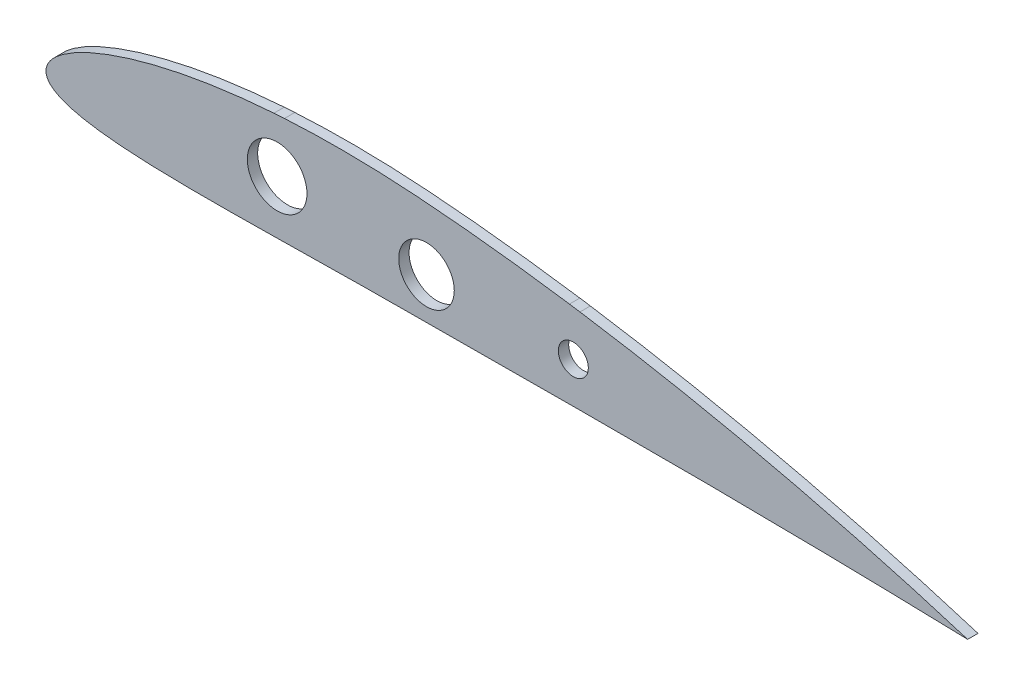
SolidWorks part; units mm, degrees
material "Фанера"
ref_plane "Front Plane" through (0, 0, 0) normal (0, 0, 1) x (1, 0, 0)
ref_plane "Top Plane" through (0, 0, 0) normal (0, 1, 0) x (1, 0, 0)
ref_plane "Right Plane" through (0, 0, 0) normal (1, 0, 0) x (0, 0, -1)
sketch "Эскиз1" plane through (0, 0, 0) normal (0, 0, 1) x (1, 0, 0)
  line L0 (150.3512, 128.259) -> (147.6767, 128.661)
  line L1 (255.981, 105.8183) -> (150.7263, 130.2251) construction
  line L2 (69.8251, 105.8135) -> (147.0441, 106.4426) construction
  line L3 (6.1919, 114.8477) -> (66.9719, 105.7712) construction
  line L4 (68.006, 135.3847) -> (6.1919, 114.8477) construction
  line L5 (68.3924, 133.4055) -> (14.7673, 115.5893) construction
  line L6 (69.8021, 107.8133) -> (147.0317, 108.4426) construction
  line L7 (147.8895, 130.6515) -> (70.8642, 135.5703) construction
  line L8 (67.001, 103.7714) -> (69.8554, 103.8137) construction
  line L9 (70.7405, 137.5665) -> (67.8703, 137.3801) construction
  line L10 (151.028, 132.2022) -> (148.1867, 132.6293) construction
  line L11 (147.0528, 104.4426) -> (149.9045, 104.4548) construction
  line L12 (147.6767, 128.661) -> (70.8653, 133.5662) construction
  line L13 (240.4166, 107.3743) -> (150.3512, 128.259) construction
  line L14 (149.8962, 106.4548) -> (255.959, 105.1887) construction
  line L15 (149.9039, 108.4548) -> (240.4166, 107.3743) construction
  line L16 (150.7263, 130.2251) -> (147.8895, 130.6515) construction
  line L17 (147.0441, 106.4426) -> (149.8962, 106.4548) construction
  line L18 (66.9719, 105.7712) -> (69.8251, 105.8135) construction
  line L19 (70.8642, 135.5703) -> (68.006, 135.3847) construction
  line L20 (67.1056, 107.7734) -> (69.8021, 107.8133) construction
  line L21 (70.8653, 133.5662) -> (68.3924, 133.4055) construction
  line L22 (147.0317, 108.4426) -> (149.9039, 108.4548) construction
  line L23 (14.7673, 115.5893) -> (67.1056, 107.7734) construction
  line L24 (150.6664, 129.8296) -> (147.8304, 130.2559)
  line L25 (70.8877, 135.171) -> (68.0343, 134.9857)
  line L26 (66.966, 106.1712) -> (69.8191, 106.2134)
  line L27 (147.0423, 106.8426) -> (149.8946, 106.8548)
  arc A0 (240.4166, 107.3743) -> (240.4166, 107.3743) centre (240.4166, 107.3743) ccw
  arc A1 (255.3129, 105.6068) -> (255.3129, 105.6068) centre (255.3129, 105.6068) ccw
  circle A2 centre (148.8681, 117.845) radius 4.05
  circle A3 centre (109.2326, 117.845) radius 7.5
  circle A4 centre (68.9168, 120.6369) radius 8.05
  arc A6 (256.3721, 103.1764) -> (256.8714, 107.636) centre (255.6552, 105.5145) ccw construction
  arc A8 (255.959, 105.1887) -> (255.981, 105.8183) centre (255.6552, 105.5145) ccw construction
  spline S0 degree 1 poles (147.8304, 130.2559) (70.8877, 135.171) knots 0 0 1 1 construction
  spline S1 degree 1 poles (68.0343, 134.9857) (6.5854, 114.7729) knots 0 0 1 1 construction
  spline S2 degree 1 poles (6.5854, 114.7729) (66.966, 106.1712) knots 0 0 1 1 construction
  spline S3 degree 1 poles (69.8191, 106.2134) (147.0423, 106.8426) knots 0 0 1 1 construction
  spline S4 degree 1 poles (149.8946, 106.8548) (255.3129, 105.6068) knots 0 0 1 1 construction
  spline S5 degree 1 poles (255.3129, 105.6068) (150.6664, 129.8296) knots 0 0 1 1 construction
  spline S6 degree 3 poles (147.8304, 130.2559) (141.4614, 131.1985) (128.6934, 132.8864) (112.6704, 134.4616) (99.827, 135.315) (86.964, 135.7313) (77.3083, 135.5495) (70.8877, 135.171) knots 0.429725 0.429725 0.429725 0.429725 0.504545 0.579365 0.616774 0.654184 0.729004 0.729004 0.729004 0.729004
  spline S7 degree 3 poles (68.0343, 134.9857) (62.4663, 134.5901) (54.1288, 133.7002) (43.1252, 131.8029) (34.9538, 129.9771) (26.9072, 127.676) (20.368, 125.2621) (15.3365, 122.8884) (11.7396, 120.808) (8.9915, 118.6964) (7.4817, 116.8862) (6.9154, 115.8582) (6.7079, 115.2743) (6.6255, 114.9369) (6.5854, 114.7729) knots 0.740091 0.740091 0.740091 0.740091 0.805048 0.837527 0.870006 0.902484 0.934963 0.951202 0.967442 0.983681 0.991801 0.995861 0.99789 0.99992 0.99992 0.99992 0.99992
  spline S8 degree 3 poles (6.5854, 114.7729) (6.5637, 114.6143) (6.519, 114.2854) (6.5148, 113.7109) (6.7419, 112.6615) (7.6602, 111.4099) (9.2591, 110.3083) (11.0446, 109.4874) (12.9222, 108.8501) (15.4901, 108.1728) (18.7685, 107.5586) (22.7454, 107.0432) (28.0773, 106.5574) (34.7696, 106.2135) (42.8135, 106.0372) (50.8627, 106.0061) (58.9136, 106.0623) (64.282, 106.1325) (66.966, 106.1712) knots 0.000081 0.000081 0.000081 0.000081 0.002067 0.004053 0.008026 0.01597 0.023915 0.031859 0.039804 0.047748 0.063637 0.079526 0.095416 0.127194 0.158972 0.19075 0.222528 0.254306 0.254306 0.254306 0.254306
  spline S9 degree 3 poles (69.8191, 106.2134) (76.2539, 106.311) (85.9048, 106.4721) (98.7779, 106.6108) (111.6511, 106.6495) (127.7354, 106.7325) (140.607, 106.8137) (147.0423, 106.8426) knots 0.265565 0.265565 0.265565 0.265565 0.341733 0.379817 0.417901 0.494069 0.570237 0.570237 0.570237 0.570237
  spline S10 degree 3 poles (149.8946, 106.8548) (158.6803, 106.89) (176.2516, 106.9163) (202.6097, 106.7306) (228.9647, 106.2926) (246.5305, 105.8506) (255.3129, 105.6068) knots 0.58149 0.58149 0.58149 0.58149 0.685469 0.789448 0.893427 0.997406 0.997406 0.997406 0.997406
  spline S11 degree 3 poles (255.3129, 105.6068) (246.7563, 108.2609) (229.5444, 113.257) (203.4702, 119.7998) (177.1786, 125.4044) (159.5222, 128.478) (150.6664, 129.8296) knots 0.002228 0.002228 0.002228 0.002228 0.106325 0.210423 0.31452 0.418617 0.418617 0.418617 0.418617
  spline S12 degree 3 poles (4.2245, 115.2218) (4.2126, 115.1351) (4.1901, 114.9728) (4.1369, 114.5596) (4.0997, 113.8715) (4.1934, 113.0746) (4.4478, 112.0722) (5.0329, 110.8962) (5.9577, 109.8121) (6.9592, 108.9756) (8.333, 108.0935) (10.0616, 107.291) (12.1329, 106.5788) (14.8842, 105.8458) (18.3089, 105.1999) (22.402, 104.6657) (26.4841, 104.2911) (30.5571, 104.0277) (35.978, 103.7862) (42.7402, 103.6379) (50.8379, 103.6058) (58.9249, 103.6622) (64.3084, 103.7327) (67.001, 103.7714) knots -0.000405 -0.000405 -0.000405 -0.000405 0.00059 0.001585 0.003575 0.005565 0.007555 0.011535 0.015514 0.019494 0.023474 0.031434 0.039394 0.047354 0.063273 0.079193 0.095112 0.111032 0.126952 0.158791 0.19063 0.222469 0.254308 0.254308 0.254308 0.254308 construction
  spline S13 degree 3 poles (67.8703, 137.3801) (65.0503, 137.1797) (59.4186, 136.6785) (50.9968, 135.5967) (42.6198, 134.1508) (34.309, 132.2908) (27.4644, 130.3322) (22.0663, 128.4455) (18.0689, 126.8357) (14.1437, 124.9752) (10.9598, 123.1311) (8.5154, 121.3532) (7.0522, 120.0467) (5.9644, 118.8218) (5.3324, 117.9305) (4.8996, 117.1691) (4.5854, 116.5037) (4.3875, 115.8781) (4.2866, 115.4769) (4.246, 115.3096) (4.2245, 115.2218) knots 0.740067 0.740067 0.740067 0.740067 0.772609 0.80515 0.837691 0.870232 0.902774 0.919044 0.935315 0.951586 0.967856 0.975992 0.984127 0.988195 0.992262 0.994296 0.99633 0.998364 0.999381 1.000398 1.000398 1.000398 1.000398 construction
  spline S14 degree 3 poles (148.1867, 132.6293) (141.7912, 133.5759) (128.9685, 135.2709) (112.884, 136.8527) (99.9444, 137.7126) (86.9715, 138.1325) (77.2213, 137.9485) (70.7405, 137.5665) knots 0.429706 0.429706 0.429706 0.429706 0.504536 0.579367 0.616782 0.654197 0.729027 0.729027 0.729027 0.729027 construction
  spline S15 degree 3 poles (256.8714, 107.636) (248.2169, 110.3216) (230.8173, 115.4068) (204.446, 122.039) (177.8555, 127.7216) (159.9886, 130.8346) (151.028, 132.2022) knots -0.001207 -0.001207 -0.001207 -0.001207 0.10375 0.208706 0.313663 0.418619 0.418619 0.418619 0.418619 construction
  spline S16 degree 3 poles (149.9045, 104.4548) (158.7785, 104.4903) (176.5281, 104.5165) (203.1441, 104.3248) (229.757, 103.8766) (247.5013, 103.4229) (256.3721, 103.1764) knots 0.581491 0.581491 0.581491 0.581491 0.686581 0.79167 0.89676 1.001849 1.001849 1.001849 1.001849 construction
  spline S17 degree 3 poles (69.8554, 103.8137) (76.2881, 103.9112) (85.9421, 104.0724) (98.7946, 104.2108) (111.6509, 104.2495) (127.7557, 104.3325) (140.6187, 104.4137) (147.0528, 104.4426) knots 0.265565 0.265565 0.265565 0.265565 0.341733 0.379817 0.4179 0.494068 0.570236 0.570236 0.570236 0.570236 construction
  spline S24 degree 3 poles (255.981, 105.8183) (255.1452, 106.0776) (252.7344, 106.8257) (248.4483, 108.1259) (242.96, 109.7477) (236.9465, 111.469) (230.6793, 113.2037) (224.3094, 114.9057) (217.8951, 116.5587) (211.4569, 118.157) (205.0023, 119.6987) (198.5346, 121.1828) (192.0557, 122.6086) (185.5671, 123.9752) (179.0705, 125.2817) (172.5672, 126.5268) (166.0589, 127.7093) (159.5471, 128.8277) (154.4349, 129.6536) (151.4938, 130.108) (150.7263, 130.2251) knots 0 0 0 0 0.010162 0.029313 0.052012 0.076619 0.101948 0.127526 0.153184 0.178868 0.204558 0.230246 0.255926 0.281594 0.307246 0.332878 0.358485 0.384061 0.409603 0.418619 0.418619 0.418619 0.418619 construction
  spline S25 degree 3 poles (149.8962, 106.4548) (151.0697, 106.4595) (154.5381, 106.4723) (160.2987, 106.4873) (167.1755, 106.4936) (174.0453, 106.4866) (180.9094, 106.465) (187.7693, 106.4278) (194.6263, 106.3745) (201.4814, 106.3045) (208.3355, 106.2177) (217.4659, 106.0799) (226.5694, 105.9098) (235.5825, 105.7122) (242.0508, 105.5578) (247.9425, 105.407) (252.5192, 105.2842) (255.0798, 105.2131) (255.959, 105.1887) knots 0.58149 0.58149 0.58149 0.58149 0.59538 0.622543 0.649673 0.676775 0.703855 0.730919 0.757971 0.785018 0.812062 0.839103 0.893099 0.919831 0.94581 0.969681 0.98959 1 1 1 1 construction
  spline S26 degree 3 poles (69.8251, 105.8135) (70.1857, 105.8189) (72.8406, 105.8595) (77.7874, 105.9382) (84.6559, 106.0429) (91.5023, 106.1327) (98.3304, 106.2005) (105.1587, 106.2352) (112.0058, 106.2499) (118.883, 106.2851) (125.7838, 106.3242) (132.6989, 106.366) (139.7863, 106.4072) (144.5679, 106.4315) (147.0441, 106.4426) knots 0.265565 0.265565 0.265565 0.265565 0.269834 0.296993 0.324123 0.351139 0.378036 0.404946 0.431961 0.459078 0.486347 0.513641 0.540929 0.570237 0.570237 0.570237 0.570237 construction
  spline S27 degree 3 poles (6.1919, 114.8477) (6.158, 114.6008) (6.0902, 114.1069) (6.1694, 113.3417) (6.4146, 112.5783) (6.8536, 111.8363) (7.4788, 111.1398) (8.2841, 110.4896) (9.2784, 109.8798) (10.4882, 109.2993) (11.964, 108.7389) (13.7853, 108.1919) (16.0678, 107.6555) (18.9581, 107.1364) (22.5962, 106.6558) (27.0464, 106.2459) (32.2488, 105.9348) (38.0427, 105.7329) (44.2433, 105.6313) (50.7063, 105.6105) (57.3406, 105.6492) (62.7802, 105.7125) (66.003, 105.7573) (66.9719, 105.7712) knots 0 0 0 0 0.002941 0.005884 0.009016 0.012365 0.016008 0.020037 0.024574 0.029784 0.035897 0.04324 0.052276 0.063635 0.077983 0.095698 0.11652 0.139661 0.164312 0.189919 0.216157 0.242838 0.254307 0.254307 0.254307 0.254307 construction
  spline S28 degree 3 poles (68.006, 135.3847) (66.8126, 135.2999) (63.6237, 135.0487) (58.4686, 134.5329) (52.5772, 133.7756) (46.793, 132.8557) (41.1539, 131.7728) (35.7197, 130.533) (30.584, 129.1556) (25.8745, 127.6815) (21.7278, 126.1743) (18.2359, 124.7076) (15.4053, 123.3395) (13.1621, 122.0961) (11.3946, 120.9731) (9.9961, 119.9509) (8.8828, 119.0062) (7.9974, 118.1179) (7.2991, 117.2701) (6.7718, 116.4486) (6.3879, 115.6507) (6.2553, 115.1075) (6.1919, 114.8477) knots 0.740091 0.740091 0.740091 0.740091 0.753983 0.777235 0.800246 0.822951 0.845237 0.866916 0.887662 0.906968 0.924203 0.938879 0.950932 0.960693 0.968647 0.975233 0.980795 0.985584 0.989782 0.993521 0.996902 1 1 1 1 construction
  spline S29 degree 3 poles (147.8895, 130.6515) (147.4311, 130.7194) (144.8039, 131.1052) (140.0082, 131.7785) (133.5004, 132.6198) (127.0013, 133.3854) (120.5131, 134.0729) (114.0543, 134.6743) (107.657, 135.196) (101.3381, 135.605) (95.0879, 135.8768) (88.882, 136.0122) (82.7096, 136.0098) (76.7059, 135.8678) (72.7625, 135.6822) (70.8642, 135.5703) knots 0.429724 0.429724 0.429724 0.429724 0.435104 0.460559 0.485959 0.511303 0.536552 0.561723 0.586629 0.611085 0.635251 0.659272 0.683164 0.706922 0.729004 0.729004 0.729004 0.729004 construction
  dimension "D1" = 16.1
  dimension "D2" = 8.1
  dimension "D4" = 15
  dimension "D3" = 0.4
  dimension "D5" = 2
extrude "Бобышка-Вытянуть1" add sketch "Эскиз1" along normal mid plane 2.8 contours S10 S11 L24 S6 L25 S7 S8 L26 S9 L27 A2 A4
